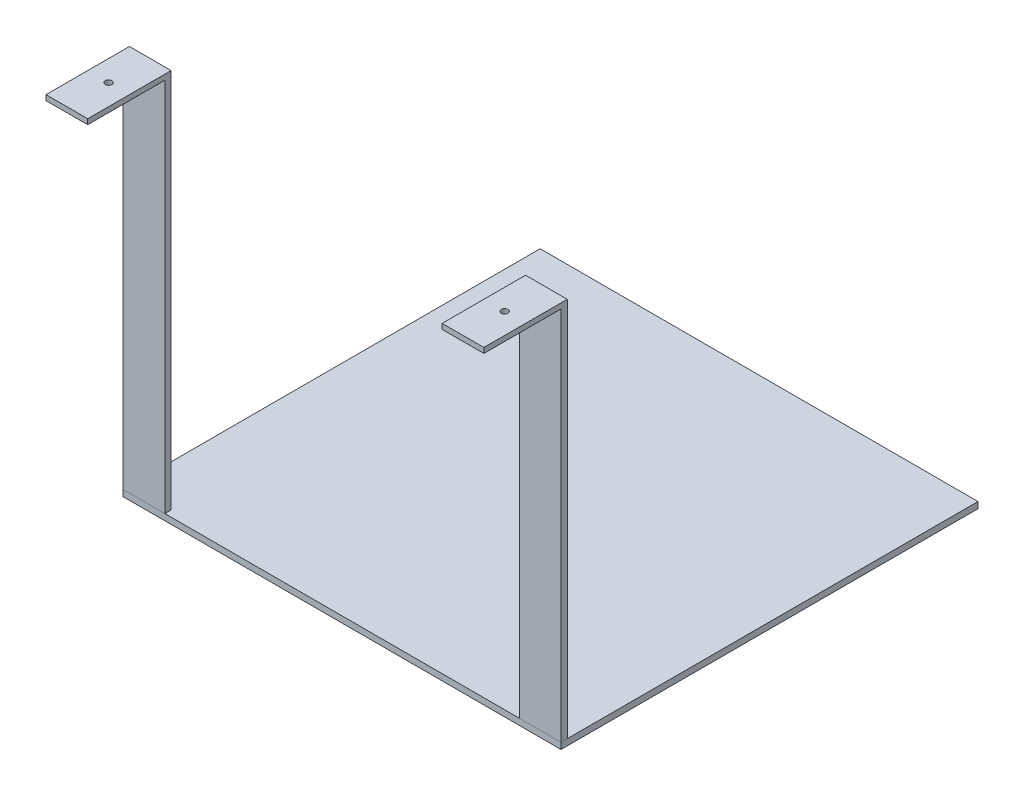
SolidWorks part; units mm, degrees
ref_plane "前视基准面" through (0, 0, 0) normal (0, 0, 1) x (1, 0, 0)
ref_plane "上视基准面" through (0, 0, 0) normal (0, 1, 0) x (1, 0, 0)
ref_plane "右视基准面" through (0, 0, 0) normal (1, 0, 0) x (0, 0, -1)
sketch "草图1" plane through (0, 0, 0) normal (0, 1, 0) x (1, 0, 0)
  line L0 (95, 0) -> (95, 17.9672) construction
  line L5 (10, -20) -> (-10, -20)
  line L6 (10, -20) -> (10, 20)
  line L7 (10, 20) -> (-10, 20)
  line L8 (-10, -20) -> (-10, 20)
  line L9 (10, -20) -> (-10, 20) construction
  line L10 (10, 20) -> (-10, -20) construction
  line L11 (180, 20) -> (200, -20) construction
  line L12 (180, -20) -> (200, 20) construction
  line L13 (200, -20) -> (200, 20)
  line L14 (180, 20) -> (200, 20)
  line L15 (180, -20) -> (180, 20)
  line L16 (180, -20) -> (200, -20)
  circle A0 centre (0, 0) radius 1.6
  circle A3 centre (190, 0) radius 1.6
  point P0 (0, 0)
  dimension "D1" = 20
  dimension "D2" = 40
  dimension "D3" = 95
extrude "凸台-拉伸1" add sketch "草图1" along normal blind 2.5
sketch "草图2" plane through (0, 0, 0) normal (0, -1, 0) x (1, 0, 0)
  line L0 (-10, -20) -> (-10, 20) construction
  line L1 (-10, -17) -> (10, -17)
  line L2 (-10, -17) -> (-10, -20)
  line L3 (-10, -20) -> (10, -20)
  line L4 (10, -17) -> (10, -20)
  line L5 (95, -996.4167) -> (95, 49003.5833) construction
  line L6 (180, -17) -> (180, -20)
  line L7 (200, -20) -> (180, -20)
  line L8 (200, -17) -> (200, -20)
  line L9 (200, -17) -> (180, -17)
  dimension "D1" = 3
  dimension "D2" = 95
extrude "凸台-拉伸2" add sketch "草图2" along normal blind 180 contours L2 L1 L4 L3 | L9 L6 L7 L8
sketch "草图3" plane through (0, -180, 0) normal (0, -1, 0) x (1, 0, 0)
  line L0 (200, -17) -> (200, -20) construction
  line L1 (-10, -17) -> (200, -17)
  line L2 (-10, -17) -> (-10, -217)
  line L3 (-10, -217) -> (200, -217)
  line L4 (200, -17) -> (200, -217)
  line L5 (-10, -17) -> (-10, 20) construction
  line L7 (-10, -17) -> (10, -17) construction
  point P8 (-10, 1.5)
  dimension "D1" = 0
  dimension "D2" = 0
  dimension "D3" = 0
  dimension "D4" = 200
extrude "凸台-拉伸3" add sketch "草图3" along normal blind 3 separate body contours L2 L1 L4 L3
